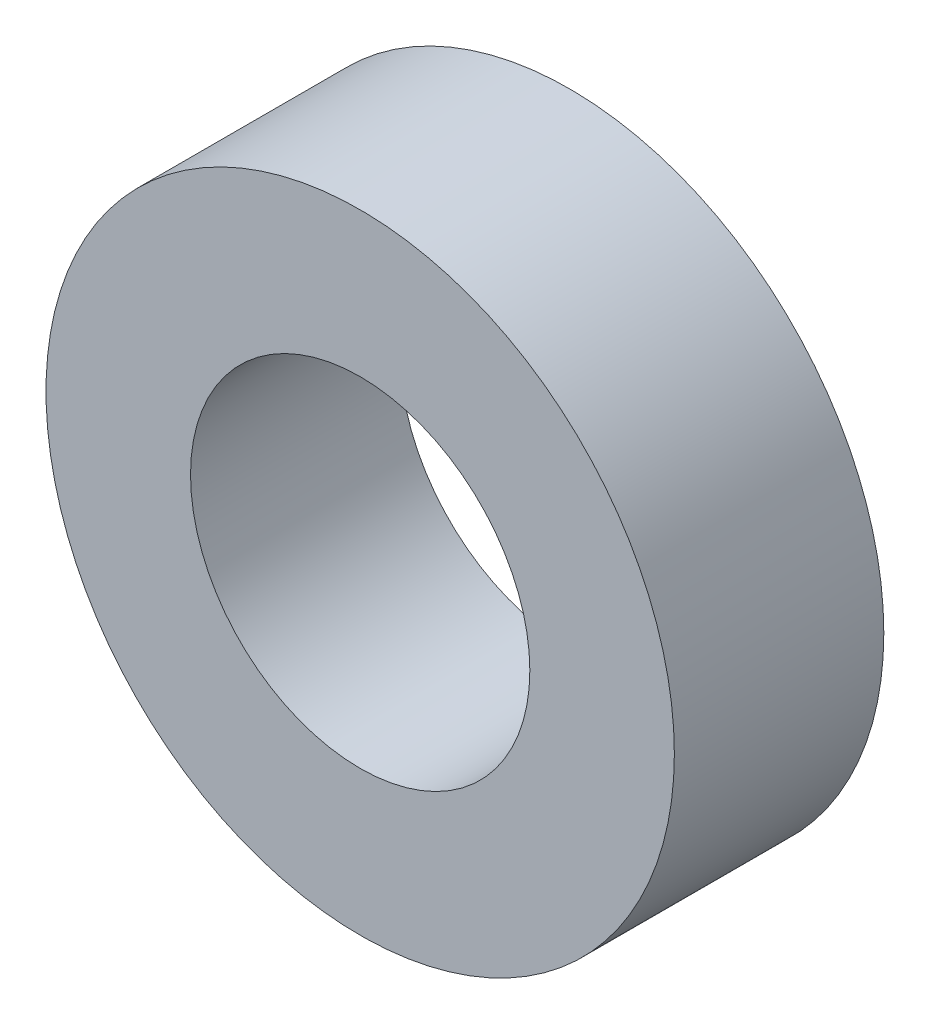
SolidWorks part; units mm, degrees
material "ABS"
ref_plane "Front Plane" through (0, 0, 0) normal (0, 0, 1) x (1, 0, 0)
ref_plane "Top Plane" through (0, 0, 0) normal (0, 1, 0) x (1, 0, 0)
ref_plane "Right Plane" through (0, 0, 0) normal (1, 0, 0) x (0, 0, -1)
sketch "Sketch1" plane through (0, 0, 0) normal (0, 0, 1) x (1, 0, 0)
  circle A0 centre (0, 0) radius 7.5
  circle A1 centre (0, 0) radius 4.05
  dimension "D1" = 15
  dimension "D2" = 8.1
extrude "Boss-Extrude1" add sketch "Sketch1" along normal blind 5
